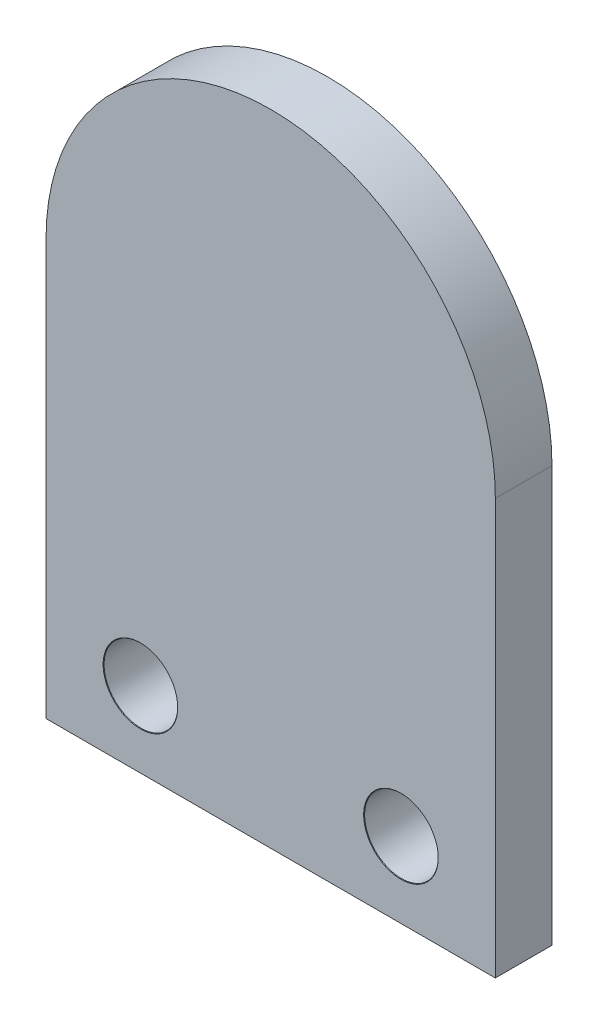
SolidWorks part; units mm, degrees
ref_plane "Front Plane" through (0, 0, 0) normal (0, 0, 1) x (1, 0, 0)
ref_plane "Top Plane" through (0, 0, 0) normal (0, 1, 0) x (1, 0, 0)
ref_plane "Right Plane" through (0, 0, 0) normal (1, 0, 0) x (0, 0, -1)
sketch "Sketch1" plane through (0, 0, 0) normal (0, 0, 1) x (1, 0, 0)
  line L0 (-11.9, 0) -> (-11.9, -22)
  line L1 (-11.9, -22) -> (11.9, -22)
  line L2 (11.9, -22) -> (11.9, 0)
  arc A0 (11.9, 0) -> (-11.9, 0) centre (0, 0) ccw
  dimension "D1" = 22
  dimension "D2" = 23.8
extrude "Boss-Extrude1" add sketch "Sketch1" along normal blind 3
sketch "Sketch2" plane through (0, 0, 0) normal (0, 0, -1) x (-1, 0, 0)
  circle A0 centre (0, 0) radius 6 construction
  circle A1 centre (0, 6) radius 1.95
  circle A2 centre (6, 0) radius 1.95
  circle A3 centre (0, -6) radius 1.95
  circle A4 centre (-6, 0) radius 1.95
  point P14 (0, 0)
  dimension "D1" = 12
  dimension "D2" = 3.9
  dimension "D3" = 4
extrude "Boss-Extrude2" add sketch "Sketch2" along normal blind 3
hole_wizard "M3.5 Clearance Hole1" positions "Sketch3" profile "Sketch4" hole size "M3.5" standard "ANSI Metric" end condition through all
sketch "Sketch3" plane through (0, 0, 3) normal (0, 0, 1) x (1, 0, 0)
  point P0 (6.9, -18)
  point P3 (-6.9, -18)
sketch "Sketch4" plane through (6.9, -18, 3) normal (1, 0, 0) x (0, -1, 0)
  line L0 (0, 0) -> (0, 6)
  line L1 (0, 6) -> (1.95, 6)
  line L2 (1.95, 6) -> (1.95, 0.025)
  line L3 (1.95, 0.025) -> (1.975, 0)
  line L5 (1.975, 0) -> (0, 0)
  line L6 (-1.95, 0.025) -> (-1.975, 0) construction
  line L11 (0, -6.35) -> (0, 107.95) construction
  dimension "Thru Hole Dia." = 3.9
  dimension "Thru Hole Depth" = 6
  dimension "Near C'Sink Dia." = 3.95
  dimension "Near C'Sink Angle" = 90
